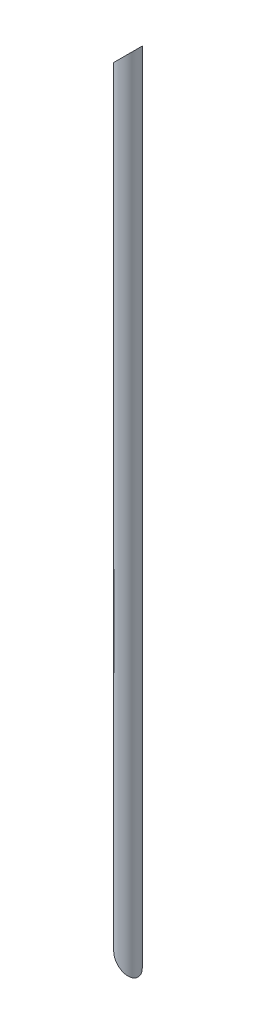
SolidWorks part; units mm, degrees
ref_plane "Plano frontal" through (0, 0, 0) normal (0, 0, 1) x (1, 0, 0)
ref_plane "Plano superior" through (0, 0, 0) normal (0, 1, 0) x (1, 0, 0)
ref_plane "Plano direito" through (0, 0, 0) normal (1, 0, 0) x (0, 0, -1)
sketch "Esboço2" plane through (0, 0, 0) normal (0, 0, 1) x (1, 0, 0)
  line L0 (0, 0) -> (0, 2530.71) construction
  line L1 (31.75, 0) -> (31.75, 2530.71)
  line L2 (31.75, 2530.71) -> (0, 2530.71)
  line L3 (31.75, 0) -> (0, 0)
  line L4 (0, 0) -> (0, 2530.71)
  dimension "D1" = 31.75
  dimension "D2" = 2530.71
revolve "Revolução2" add sketch "Esboço2" angle 360 about L0
sketch "Esboço3" plane through (0, 0, 0) normal (0, 0, 1) x (1, 0, 0)
  line L0 (-31.75, 2530.71) -> (31.75, 2530.71)
  line L1 (31.75, 2530.71) -> (-31.75, 2467.21)
  line L2 (-31.75, 2530.71) -> (-31.75, 0) construction
  line L3 (-31.75, 2467.21) -> (-31.75, 2530.71)
  line L4 (31.75, 0) -> (-31.75, 63.5)
  line L8 (-31.75, 63.5) -> (-31.75, 0)
  line L9 (-31.75, 0) -> (31.75, 0)
extrude "Corte-extrusão1" cut sketch "Esboço3" against normal through all both and the other way through all
sketch "Esboço9" plane through (0, 0, 0) normal (0, 1, 0) x (1, 0, 0)
  circle A0 centre (0, 0) radius 30.75
  dimension "D1" = 61.5
extrude "Corte-extrusão6" cut sketch "Esboço9" along normal through all
